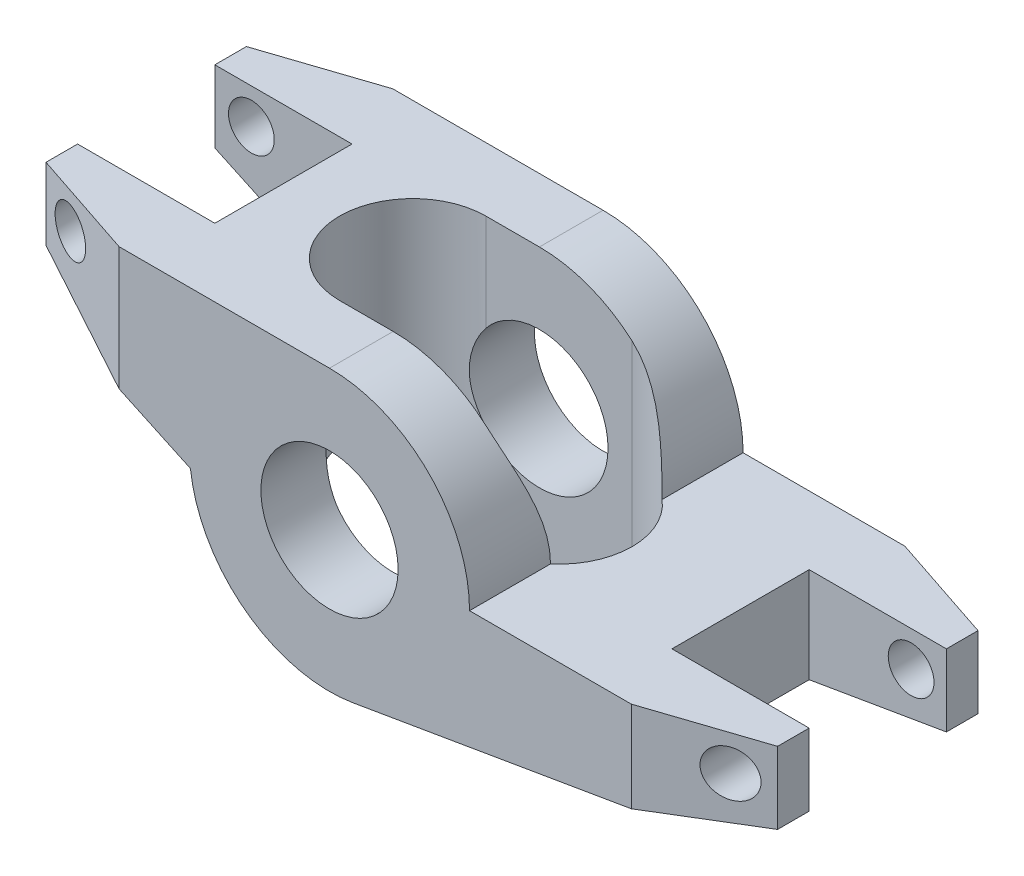
SolidWorks part; units mm, degrees
ref_plane "Front Plane" through (0, 0, 0) normal (0, 0, 1) x (1, 0, 0)
ref_plane "Top Plane" through (0, 0, 0) normal (0, 1, 0) x (1, 0, 0)
ref_plane "Right Plane" through (0, 0, 0) normal (1, 0, 0) x (0, 0, -1)
sketch "Sketch2" plane through (0, 0, 0) normal (0, 0, 1) x (1, 0, 0)
  line L0 (0, 9.725) -> (-22.23, 9.725)
  line L1 (-22.23, 9.725) -> (-22.23, 4.725)
  line L2 (-22.23, 4.725) -> (-9.6583, -1.1373)
  line L3 (9.725, 0) -> (28.58, 0)
  line L4 (28.58, 0) -> (28.58, -5)
  line L5 (28.58, -5) -> (1.6319, -9.5871)
  arc A0 (9.725, 0) -> (0, 9.725) centre (0, 0) ccw
  circle A1 centre (0, 0) radius 4.765
  arc A2 (-9.6583, -1.1373) -> (1.6319, -9.5871) centre (0, 0) ccw
  dimension "D1" = 19.45
  dimension "D2" = 9.53
  dimension "D3" = 22.23
  dimension "D4" = 5
  dimension "D5" = 25
  dimension "D6" = 28.58
extrude "Boss-Extrude1" add sketch "Sketch2" along normal mid plane 19
chamfer "Chamfer1" distance 7.62 distance2 2.54 2 edges at (28.58, -2.5, -9.5) (-22.23, 7.225, -9.5)
chamfer "Chamfer2" distance 2.54 distance2 7.62 2 edges at (28.58, -2.5, 9.5) (-22.23, 7.225, 9.5)
sketch "Sketch3" plane through (0, 9.725, 0) normal (0, 1, 0) x (1, 0, 0)
  line L10 (-22.23, -6.96) -> (-22.23, 6.96) construction
  line L11 (-22.23, 4.765) -> (-12.7, 4.765)
  line L12 (-22.23, 4.765) -> (-22.23, -4.765)
  line L13 (-22.23, -4.765) -> (-12.7, -4.765)
  line L14 (-12.7, 4.765) -> (-12.7, -4.765)
  line L15 (28.58, -6.96) -> (28.58, 6.96) construction
  line L16 (28.58, 4.765) -> (19.05, 4.765)
  line L17 (28.58, 4.765) -> (28.58, -4.765)
  line L18 (28.58, -4.765) -> (19.05, -4.765)
  line L19 (19.05, 4.765) -> (19.05, -4.765)
  point P12 (-12.7, 0)
  point P14 (19.05, 0)
  dimension "D1" = 9.53
extrude "Cut-Extrude1" cut sketch "Sketch3" against normal through all
sketch "Sketch4" plane through (0, 0, 0) normal (0, 1, 0) x (1, 0, 0)
  line L0 (-3.72, 0) -> (6.44, 0) construction
  line L1 (-3.72, 5.08) -> (6.44, 5.08)
  line L2 (-3.72, -5.08) -> (6.44, -5.08)
  line L3 (-12.7, -4.765) -> (-12.7, 4.765) construction
  arc A0 (-3.72, 5.08) -> (-3.72, -5.08) centre (-3.72, 0) ccw
  arc A1 (6.44, -5.08) -> (6.44, 5.08) centre (6.44, 0) ccw
  point P3 (1.36, 0)
  dimension "D3" = 5.08
  dimension "D1" = 8.98
  dimension "D2" = 10.16
extrude "Cut-Extrude2" cut sketch "Sketch4" against normal through all both and the other way through all
sketch "Sketch5" plane through (0, 0, 0) normal (0, 0, 1) x (1, 0, 0)
  line L0 (-22.23, 4.725) -> (-22.23, 9.725) construction
  line L1 (-22.23, 9.725) -> (-14.61, 9.725) construction
  line L2 (20.96, 0) -> (28.58, 0) construction
  line L3 (28.58, 0) -> (28.58, -5) construction
  circle A0 centre (-19.69, 7.275) radius 1.59
  circle A1 centre (26.13, -2.45) radius 1.59
  dimension "D1" = 2.54
  dimension "D2" = 2.45
  dimension "D3" = 2.45
  dimension "D4" = 2.45
extrude "Cut-Extrude3" cut sketch "Sketch5" against normal through all both and the other way through all
